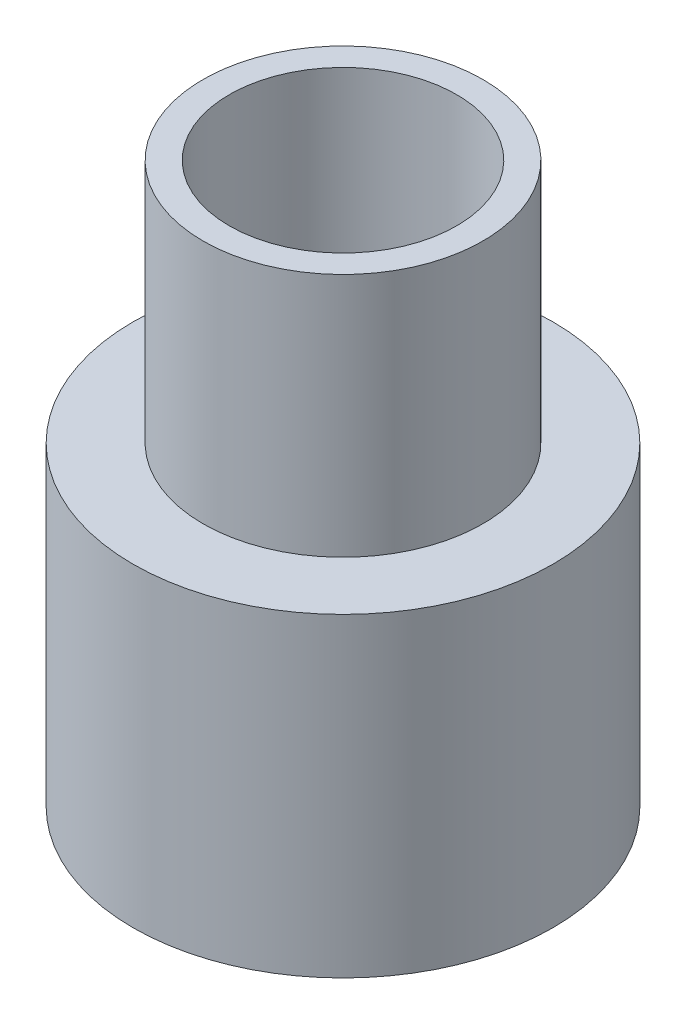
SolidWorks part; units mm, degrees
ref_plane "Alzado" through (0, 0, 0) normal (0, 0, 1) x (1, 0, 0)
ref_plane "Planta" through (0, 0, 0) normal (0, 1, 0) x (1, 0, 0)
ref_plane "Vista lateral" through (0, 0, 0) normal (1, 0, 0) x (0, 0, -1)
sketch "Croquis1" plane through (0, 0, 0) normal (0, 1, 0) x (1, 0, 0)
  circle A0 centre (0, 0) radius 6
  circle A1 centre (0, 0) radius 3.25
  dimension "D1" = 12
  dimension "D2" = 6.5
extrude "Saliente-Extruir1" add sketch "Croquis1" along normal blind 9
sketch "Croquis2" plane through (0, 9, 0) normal (0, 1, 0) x (1, 0, 0)
  circle A0 centre (0, 0) radius 4
  circle A1 centre (0, 0) radius 3.25 construction
  circle A2 centre (0, 0) radius 3.25
  dimension "D1" = 8
extrude "Saliente-Extruir2" add sketch "Croquis2" along normal blind 7
